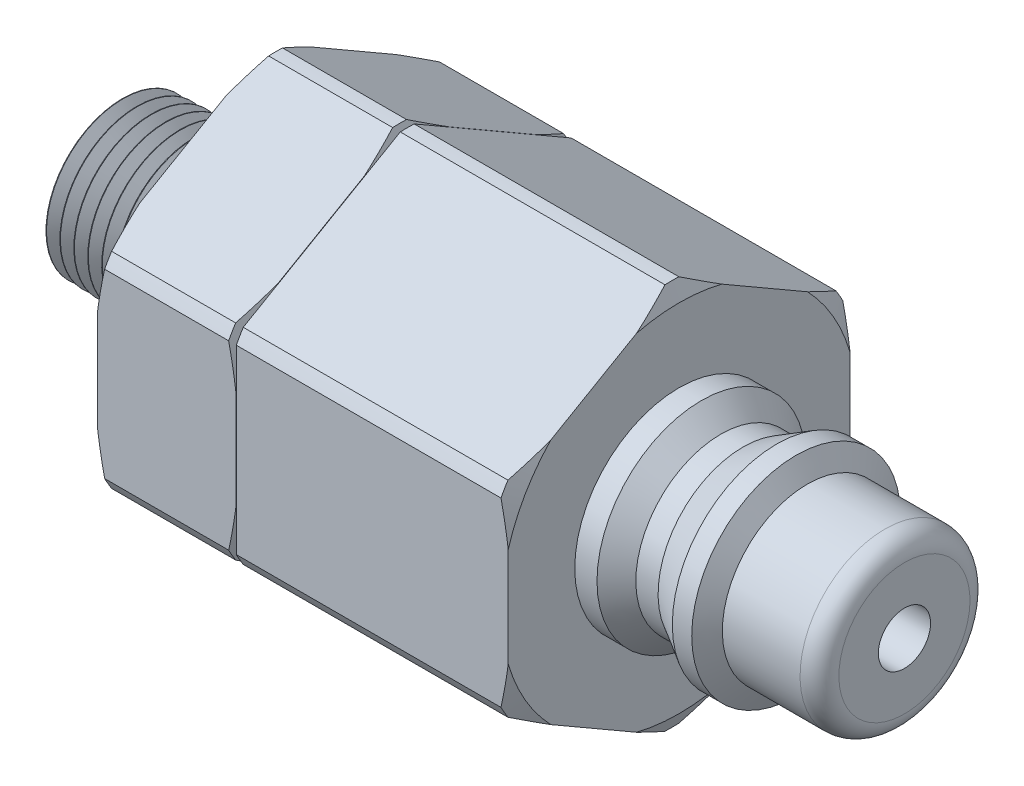
SolidWorks part; units mm, degrees
ref_plane "Front" through (0, 0, 0) normal (0, 0, 1) x (1, 0, 0)
ref_plane "Top" through (0, 0, 0) normal (0, 1, 0) x (1, 0, 0)
ref_plane "Right" through (0, 0, 0) normal (1, 0, 0) x (0, 0, -1)
sketch "Sketch1" plane through (0, 0, 0) normal (0, 0, 1) x (1, 0, 0)
  line L0 (0, 0) -> (0, 4.2025)
  line L1 (0, 4.2025) -> (0.4447, 5.0315) construction
  line L2 (0.4447, 5.0315) -> (0.9403, 4.2319) construction
  line L3 (0.9403, 4.2319) -> (1.385, 5.0609) construction
  line L4 (1.385, 5.0609) -> (1.8806, 4.2613) construction
  line L5 (0.9572, 4.2635) -> (1.368, 5.0293)
  line L6 (1.368, 5.0293) -> (1.4039, 5.0304)
  line L7 (1.4039, 5.0304) -> (1.8617, 4.2918)
  line L8 (1.8617, 4.2918) -> (1.8975, 4.2929)
  line L9 (0, 4.2025) -> (1.8806, 4.2613) construction
  line L10 (0.4447, 5.0315) -> (1.385, 5.0609) construction
  line L11 (0.2223, 4.617) -> (1.6328, 4.6611) construction
  line L12 (0, 0) -> (-4.2025, 0) construction
  line L13 (1.8975, 4.2929) -> (2.3083, 5.0587)
  line L14 (0.017, 4.2342) -> (0.4277, 4.9999)
  line L15 (0.4277, 4.9999) -> (0.4636, 5.0011)
  line L16 (0.4636, 5.0011) -> (0.9214, 4.2624)
  line L17 (0.9214, 4.2624) -> (0.9572, 4.2635)
  line L18 (0.2223, 4.617) -> (0, 4.6101) construction
  line L19 (0, 4.6101) -> (0, 4.2025) construction
  line L20 (0.2223, -4.617) -> (0, -4.6101) construction
  line L21 (0.017, 4.2342) -> (0, 4.2025)
  line L22 (2.3083, 5.0587) -> (2.3441, 5.0598)
  line L23 (2.3441, 5.0598) -> (2.802, 4.3212)
  line L24 (2.802, 4.3212) -> (2.8378, 4.3223)
  line L25 (2.8378, 4.3223) -> (3.2486, 5.0881)
  line L26 (3.2486, 5.0881) -> (3.2844, 5.0892)
  line L27 (3.2844, 5.0892) -> (3.7422, 4.3506)
  line L28 (3.7422, 4.3506) -> (3.7781, 4.3517)
  line L29 (3.7781, 4.3517) -> (4.1889, 5.1175)
  line L30 (4.1889, 5.1175) -> (4.2247, 5.1186)
  line L31 (4.2247, 5.1186) -> (4.6825, 4.38)
  line L32 (4.6825, 4.38) -> (4.7184, 4.3811)
  line L33 (4.7184, 4.3811) -> (5.1291, 5.1469)
  line L34 (5.1291, 5.1469) -> (5.165, 5.148)
  line L35 (5.165, 5.148) -> (5.6228, 4.4093)
  line L36 (5.6228, 4.4093) -> (5.6586, 4.4105)
  line L37 (5.6586, 4.4105) -> (6.0694, 5.1763)
  line L38 (6.0694, 5.1763) -> (6.1053, 5.1774)
  line L39 (6.1053, 5.1774) -> (6.5631, 4.4387)
  line L40 (6.5631, 4.4387) -> (6.5989, 4.4398)
  line L41 (6.5989, 4.4398) -> (7.0097, 5.2056)
  line L42 (7.0097, 5.2056) -> (7.0456, 5.2068)
  line L43 (7.0456, 5.2068) -> (7.5034, 4.4681)
  line L44 (7.5034, 4.4681) -> (7.5392, 4.4692)
  line L45 (7.5392, 4.4692) -> (7.95, 5.235)
  line L46 (7.95, 5.235) -> (7.9858, 5.2361)
  line L47 (7.9858, 5.2361) -> (8.4436, 4.4975)
  line L48 (8.4436, 4.4975) -> (8.4795, 4.4986)
  line L49 (8.4795, 4.4986) -> (8.8903, 5.2644)
  line L50 (8.8903, 5.2644) -> (8.9261, 5.2655)
  line L51 (8.9261, 5.2655) -> (9.3839, 4.5269)
  line L52 (9.3839, 4.5269) -> (9.4198, 4.528)
  line L53 (9.4198, 4.528) -> (9.8306, 5.2938)
  line L54 (9.8306, 5.2938) -> (9.8664, 5.2949)
  line L55 (9.8664, 5.2949) -> (10.3242, 4.5563)
  line L56 (10.3242, 4.5563) -> (10.3601, 4.5574)
  line L57 (10.3601, 4.5574) -> (10.7708, 5.3232)
  line L58 (10.7708, 5.3232) -> (10.8067, 5.3243)
  line L59 (10.8067, 5.3243) -> (11.2645, 4.5857)
  line L60 (11.2645, 4.5857) -> (11.3003, 4.5868)
  line L61 (0, 0) -> (51.562, 0) construction
  line L62 (0, 3.4163) -> (0, -3.4163) construction
  line L73 (0, 0) -> (11.3003, 0)
  line L74 (11.3003, 0) -> (11.3003, 4.5868)
  line L75 (0.4457, 5.0005) -> (0.4447, 5.0315) construction
  line L76 (1.6328, 4.6611) -> (6.7056, 4.8197) construction
  line L77 (6.7056, 4.8197) -> (6.7056, 0) construction
  line L78 (6.7056, 4.8197) -> (9.967, 4.9216) construction
  line L79 (9.967, 4.9216) -> (9.967, 0) construction
  line L80 (9.967, 4.9216) -> (9.967, 5.1435) construction
  line L81 (9.967, 5.1435) -> (11.3003, 5.1435) construction
  line L82 (11.3003, 5.1435) -> (11.3003, 4.5868) construction
  line L84 (6.7056, 4.4432) -> (9.967, 4.5451) construction
  line L87 (9.967, 4.2025) -> (0, 4.2025) construction
  point P75 (36.83, 0)
  dimension "D1" = 60
  dimension "E0" = 9.2202
  dimension "Thread Pitch" = 0.9407
  dimension "D4" = 3.58
  dimension "D2" = 0.031
  dimension "D3" = 0.0359
  dimension "L2 Thread Engagement" = 6.7056
  dimension "L4 Thread Length" = 9.967
  dimension "Pipe OD" = 10.287
  dimension "Length" = 51.562
  dimension "ID" = 6.8326
  dimension "Plug End" = 14.732
revolve "Revolve1" add sketch "Sketch1" angle 360 about L12
sketch "Sketch5" plane through (0, 0, 0) normal (0, 0, 1) x (1, 0, 0)
  line L0 (9.967, 0) -> (9.967, 5.2981)
  line L1 (9.967, 5.2981) -> (11.3003, 5.3397)
  line L2 (11.3003, 5.3397) -> (11.3003, 0)
  line L3 (11.3003, 0) -> (9.967, 0)
  line L4 (0, 0) -> (-4.2025, 0) construction
  line L5 (0, 0) -> (-4.2025, 0) construction
  line L6 (9.967, 4.9216) -> (9.967, 0) construction
  line L8 (10.7708, 5.3232) -> (10.8067, 5.3243) construction
  line L9 (11.3003, 5.1435) -> (11.3003, 4.5868) construction
  line L16 (0, 0) -> (51.562, 0) construction
revolve "Cut-Revolve2" cut sketch "Sketch5" angle 360 about L5
sketch "Sketch6" plane through (0, 0, 0) normal (0, 0, 1) x (1, 0, 0)
  line L0 (0, 0) -> (0, 4.2025) construction
  line L1 (11.3003, 5.1435) -> (0, 5.1435)
  line L2 (11.3003, 5.1435) -> (11.3003, 20.6399)
  line L3 (11.3003, 20.6399) -> (0, 20.6399)
  line L4 (0, 5.1435) -> (0, 20.6399)
revolve "Cut-Revolve3" cut sketch "Sketch6" angle 360 about L61
sketch "Sketch7" plane through (0, 0, 0) normal (0, 0, 1) x (1, 0, 0)
  line L0 (6.7056, 4.2025) -> (9.967, 5.1435)
  line L1 (6.7056, 4.8197) -> (6.7056, 0) construction
  line L2 (9.967, 4.2025) -> (0, 4.2025) construction
  line L3 (9.967, 5.1435) -> (9.967, 4.2025)
  line L4 (9.967, 4.2025) -> (6.7056, 4.2025)
revolve "Revolve2" add sketch "Sketch7" angle 360 about L61
sketch "Sketch8" plane through (9.967, 0, 0) normal (1, 0, 0) x (0, 0, -1)
  line L1 (0, 12.9049) -> (-11.176, 6.4525)
  line L2 (-11.176, 6.4525) -> (-11.176, -6.4525)
  line L3 (-11.176, -6.4525) -> (0, -12.9049)
  line L4 (0, -12.9049) -> (11.176, -6.4525)
  line L5 (11.176, -6.4525) -> (11.176, 6.4525)
  line L6 (11.176, 6.4525) -> (0, 12.9049)
  circle A0 centre (0, 0) radius 11.176 construction
  dimension "Hex" = 22.352
extrude "Extrude1" add sketch "Sketch8" along normal up to vertex (26.863 mm away) up to point (36.83, 0, 0)
sketch "Sketch9" plane through (0, 0, 0) normal (0, 0, 1) x (1, 0, 0)
  line L0 (36.83, 11.6349) -> (36.3562, 12.6509)
  line L1 (36.83, 6.4525) -> (36.83, 12.9049) construction
  line L2 (36.3562, 12.6509) -> (10.4407, 12.6509)
  line L3 (10.4407, 12.6509) -> (9.967, 11.6349)
  line L4 (9.967, 6.4525) -> (9.967, 12.9049) construction
  line L5 (9.967, 11.6349) -> (9.967, 12.9049)
  line L6 (9.967, 12.9049) -> (36.83, 12.9049)
  line L7 (36.83, 12.9049) -> (36.83, 11.6349)
  dimension "D1" = 25
  dimension "D2" = 0.254
  dimension "D3" = 1.27
revolve "Cut-Revolve4" cut sketch "Sketch9" angle 360 about L61
sketch "Sketch10" plane through (0, 0, 0) normal (0, 0, 1) x (1, 0, 0)
  line L0 (36.83, 0) -> (51.562, 0)
  line L1 (51.562, 0) -> (51.562, 5.5562)
  line L2 (51.562, 5.5562) -> (45.212, 5.5562)
  line L3 (45.212, 5.5562) -> (44.4788, 6.8262)
  line L4 (44.4788, 6.8262) -> (43.2088, 6.8262)
  line L5 (43.2088, 6.8262) -> (41.0091, 5.5562)
  line L6 (41.0091, 5.5562) -> (39.5545, 5.5562)
  line L7 (39.5545, 5.5562) -> (38.2845, 6.8262)
  line L8 (38.2845, 6.8262) -> (36.83, 6.8262)
  line L9 (36.83, 3.2355) -> (36.83, 8.0609) construction
  line L10 (36.83, 6.8262) -> (36.83, 0)
  line L11 (51.562, 5.5562) -> (51.562, -5.5562) construction
  dimension "D3" = 30
  dimension "D4" = 45
  dimension "D1" = 1.27
  dimension "A" = 11.1125
  dimension "B" = 6.35
  dimension "D2" = 60
  dimension "D5" = 1.27
revolve "Revolve3" add sketch "Sketch10" angle 360 about L12
fillet "Fillet1" radius 1.27 1 edges at (51.562, 5.5562, 0)
sketch "Sketch11" plane through (0, 0, 0) normal (0, 0, 1) x (1, 0, 0)
  line L0 (11.3003, 3.4163) -> (36.83, 1.7082)
  line L1 (0, 3.4163) -> (11.3003, 3.4163)
  line L2 (0, 3.4163) -> (0, 0)
  line L3 (0, 0) -> (6.7056, 0)
  line L4 (36.83, 1.7082) -> (51.562, 1.7082)
  line L6 (51.562, 0) -> (51.562, 5.5562) construction
  line L8 (51.562, 1.7082) -> (51.562, 0)
  line L9 (51.562, 0) -> (6.7056, 0)
  line L11 (11.3003, 0) -> (11.3003, 4.5868) construction
  line L12 (36.83, 6.8262) -> (36.83, 0) construction
  point P6 (0, 1.7082)
revolve "Cut-Revolve5" cut sketch "Sketch11" angle 360 about L12
sketch "Sketch12" plane through (0, 0, 0) normal (0, 0, 1) x (1, 0, 0)
  line L0 (0, 0) -> (51.562, 0) construction
  line L1 (19.05, 0) -> (19.05, 12.9049) construction
  line L2 (9.967, 12.9049) -> (36.83, 12.9049) construction
  line L3 (19.05, 0) -> (19.0246, 0) construction
  line L4 (19.0246, 0) -> (19.0246, 11.6349) construction
  line L5 (19.0246, 11.6349) -> (18.4324, 12.9049)
  line L6 (18.4324, 12.9049) -> (19.05, 12.9049)
  line L7 (19.05, 12.9049) -> (19.05, 5.1435)
  line L8 (19.05, 5.1435) -> (19.0246, 5.1435)
  line L9 (19.0246, 5.1435) -> (19.0246, 11.6349)
  line L10 (9.967, 5.1435) -> (11.3003, 5.1435) construction
  point P0 (19.05, 0)
  dimension "D1" = 0.0254
  dimension "D2" = 25
  dimension "F" = 19.05
revolve "Cut-Revolve6" cut sketch "Sketch12" angle 360 about L61
equation "\"D2@Sketch1\"=\"Thread Pitch@Sketch1\"*.033"
